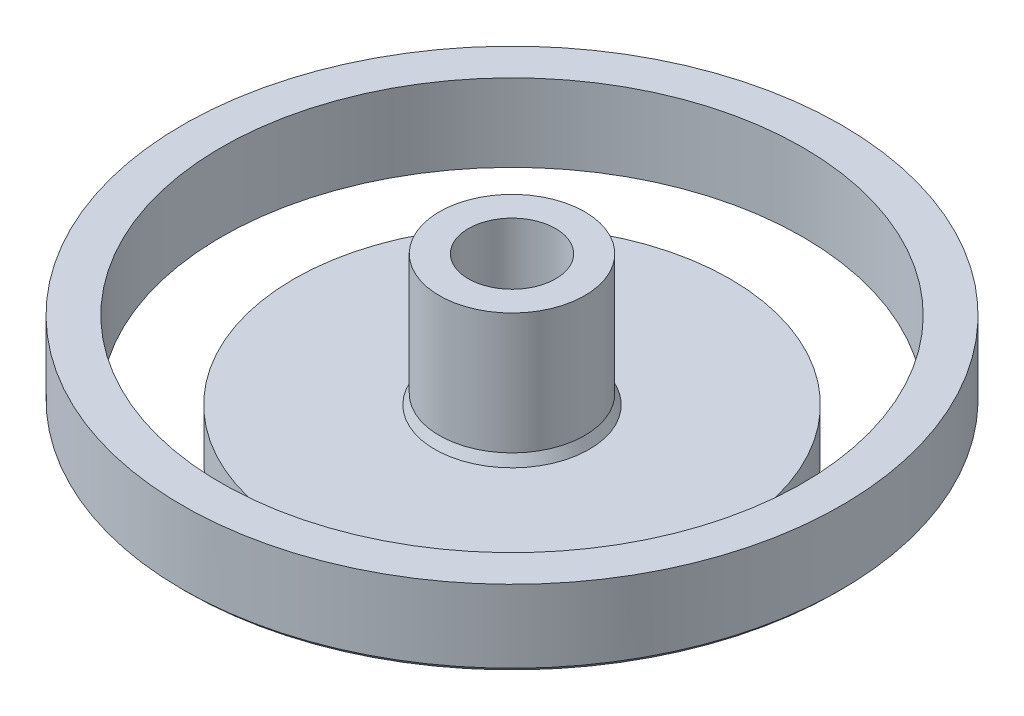
SolidWorks part; units mm, degrees
material "6061-T6 (SS)"
ref_plane "Piano frontale" through (0, 0, 0) normal (0, 0, 1) x (1, 0, 0)
ref_plane "Piano superiore" through (0, 0, 0) normal (0, 1, 0) x (1, 0, 0)
ref_plane "Piano destro" through (0, 0, 0) normal (1, 0, 0) x (0, 0, -1)
sketch "Schizzo1" plane through (0, 0, 0) normal (0, 0, 1) x (1, 0, 0)
  line L0 (0, 0) -> (0, 31.7802) construction
  line L2 (-68, 0) -> (-68, 10)
  line L3 (-68, 10) -> (-15.9412, 10)
  line L4 (-15.9412, 10) -> (-15, 12)
  line L5 (-15, 12) -> (-15, 37)
  line L6 (-15, 37) -> (-9, 37)
  line L7 (-9, 37) -> (-9, 13.5)
  line L8 (-9, 13.5) -> (-13, 5)
  line L9 (-13, 5) -> (-24, 5)
  line L10 (-24, 5) -> (-24, 0)
  line L11 (-24, 0) -> (-68, 0)
  line L12 (-18.4, 5) -> (-18.4, 6.3)
  line L13 (-18.4, 6.3) -> (-16, 6.3)
  line L14 (-16, 6.3) -> (-16, 5)
  line L15 (-34.4, 0) -> (-34.4, 1.3)
  line L16 (-34.4, 1.3) -> (-32, 1.3)
  line L17 (-32, 1.3) -> (-32, 0)
  line L18 (-68, 0) -> (-68, 26) construction
  line L19 (-68, 10) -> (-68, 26)
  line L20 (-68, 26) -> (-60, 26)
  line L21 (-29.5, 0) -> (-29.5, 1.3)
  line L22 (-60, 26) -> (-60, 10)
  line L23 (-29.5, 1.3) -> (-27.1, 1.3)
  line L24 (-27.1, 1.3) -> (-27.1, 0)
  line L25 (-45, 0) -> (-45, 10)
  point P3 (-9, 25.25)
  dimension "D1" = 48
  dimension "D2" = 26
  dimension "D3" = 18
  dimension "D4" = 8
  dimension "D5" = 10
  dimension "D6" = 5
  dimension "D7" = 30
  dimension "D8" = 25
  dimension "D9" = 27
  dimension "D10" = 8.5
  dimension "D11" = 2.4
  dimension "D12" = 1.3
  dimension "D13" = 32
  dimension "D14" = 64
  dimension "D15" = 2.5
  dimension "D16" = 90
revolve "Rivoluzione1" add sketch "Schizzo1" angle 360 about L0
chamfer "Smusso2" distance 1 angle 45 1 edges at (0, 0, -24)
fillet "Raccordo1" radius 1 1 edges at (0, 5, -24)
fillet "Raccordo2" radius 0.2 6 edges at (0, 6.3, -18.4) (0, 6.3, -16) (0, 1.3, -29.5) (0, 1.3, -27.1) (0, 1.3, -34.4) (0, 1.3, -32)
chamfer "Smusso3" distance 1 angle 45 1 edges at (0, 10, -68)
